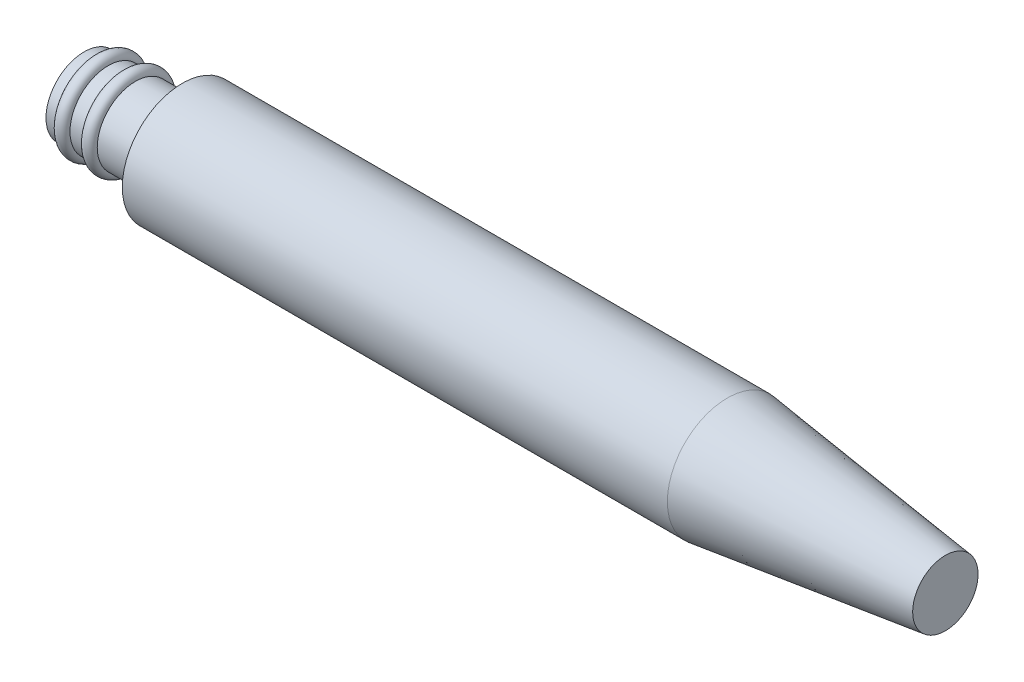
SolidWorks part; units mm, degrees
ref_plane "Front Plane" through (0, 0, 0) normal (0, 0, 1) x (1, 0, 0)
ref_plane "Top Plane" through (0, 0, 0) normal (0, 1, 0) x (1, 0, 0)
ref_plane "Right Plane" through (0, 0, 0) normal (1, 0, 0) x (0, 0, -1)
sketch "Sketch1" plane through (0, 0, 0) normal (0, 0, 1) x (1, 0, 0)
  line L0 (172.1693, 153.8126) -> (192.2353, 153.8126)
  line L1 (172.1693, 154.7016) -> (172.4233, 154.7016)
  line L2 (174.4553, 154.7016) -> (173.3631, 154.7016)
  line L3 (192.2353, 154.5746) -> (192.2353, 153.8126)
  line L4 (171.9153, 154.5746) -> (171.9153, 155.7423) construction
  line L5 (171.9153, 155.7423) -> (172.1693, 155.7423) construction
  line L6 (172.1693, 154.7016) -> (172.1693, 153.8126)
  line L7 (174.4553, 154.7016) -> (174.4553, 155.2096)
  line L8 (174.4553, 155.2096) -> (187.1553, 155.2096)
  line L10 (187.1553, 155.2096) -> (192.2353, 154.5746)
  line L11 (172.7281, 154.7016) -> (173.0583, 154.7016)
  line L13 (172.1693, 153.8126) -> (192.2353, 153.8126) construction
  arc A1 (172.7281, 154.7016) -> (172.4233, 154.7016) centre (172.5757, 154.7016) ccw
  arc A2 (173.3631, 154.7016) -> (173.0583, 154.7016) centre (173.2107, 154.7016) ccw
revolve "Revolve1" add sketch "Sketch1" angle 360 about L13
